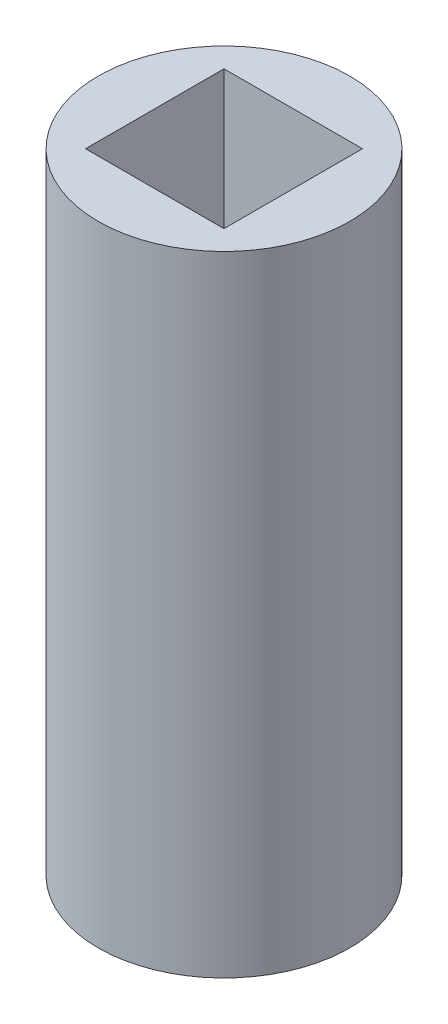
SolidWorks part; units mm, degrees
material "ABS"
ref_plane "Front Plane" through (0, 0, 0) normal (0, 0, 1) x (1, 0, 0)
ref_plane "Top Plane" through (0, 0, 0) normal (0, 1, 0) x (1, 0, 0)
ref_plane "Right Plane" through (0, 0, 0) normal (1, 0, 0) x (0, 0, -1)
sketch "Sketch1" plane through (0, 0, 0) normal (0, 1, 0) x (1, 0, 0)
  line L1 (-3.3, 3.3) -> (3.3, 3.3)
  line L2 (-3.3, 3.3) -> (-3.3, -3.3)
  line L3 (-3.3, -3.3) -> (3.3, -3.3)
  line L4 (3.3, 3.3) -> (3.3, -3.3)
  circle A0 centre (0, 0) radius 6
  point P4 (0, 3.3)
  point P6 (-3.3, 0)
  dimension "D2" = 12
  dimension "D1" = 6.6
extrude "Boss-Extrude1" add sketch "Sketch1" along normal blind 30
